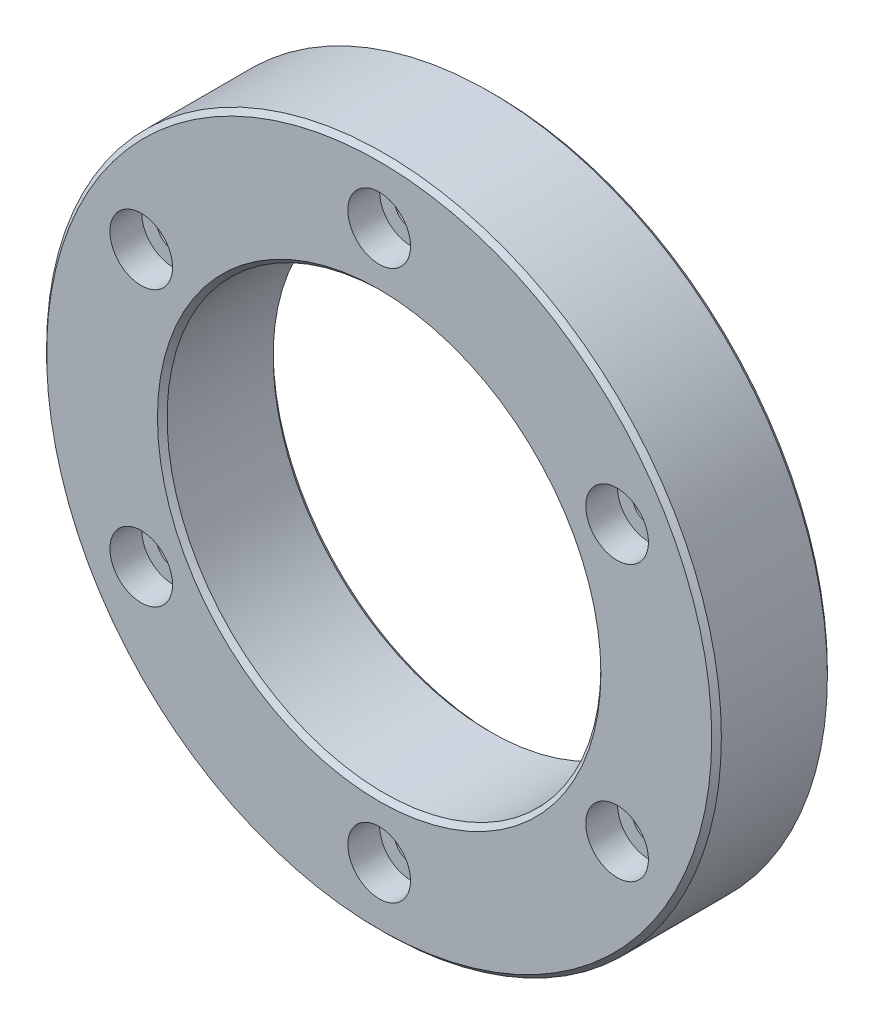
SolidWorks part; units mm, degrees
ref_plane "정면" through (0, 0, 0) normal (0, 0, 1) x (1, 0, 0)
ref_plane "윗면" through (0, 0, 0) normal (0, 1, 0) x (1, 0, 0)
ref_plane "우측면" through (0, 0, 0) normal (1, 0, 0) x (0, 0, -1)
sketch "스케치1" plane through (0, 0, 0) normal (0, 0, 1) x (1, 0, 0)
  circle A0 centre (0, 0) radius 35
  circle A1 centre (0, 0) radius 22.5
  dimension "D1" = 70
  dimension "D2" = 45
extrude "보스-돌출1" add sketch "스케치1" along normal mid plane 12
hole_wizard "M3 육각 소켓 머리 캡 나사용 카운터보어1" positions "스케치3" profile "스케치2" counterbore size "M3" standard "ISO" end condition through all
sketch "스케치3" plane through (0, 0, 6) normal (0, 0, 1) x (1, 0, 0)
  point P0 (0, 28.5)
  dimension "D1" = 28.5
sketch "스케치2" plane through (0, 28.5, 6) normal (1, 0, 0) x (0, -1, 0)
  line L0 (0, 0) -> (0, 12)
  line L1 (0, 12) -> (1.7, 12)
  line L3 (1.7, 12) -> (1.7, 3.3)
  line L4 (1.7, 3.3) -> (3.25, 3.3)
  line L5 (3.25, 3.3) -> (3.25, 0)
  line L7 (3.25, 0) -> (0, 0)
  line L11 (0, -6.35) -> (0, 107.95) construction
  dimension "°üÅë ±¸¸Û Áö¸§" = 3.4
  dimension "°üÅë ±¸¸Û ±íÀÌ" = 12
  dimension "Ä«¿îÅÍº¸¾î Áö¸§" = 6.5
  dimension "Ä«¿îÅÍº¸¾î ±íÀÌ" = 3.3
pattern_circular "원형 패턴1" count 6 over 360 about axis through (0, 0, 0) along (0, 0, 1) of "M3 육각 소켓 머리 캡 나사용 카운터보어1"
chamfer "모따기1" distance 0.5 angle 45 4 edges at (35, 0, -6) (35, 0, 6) (22.5, 0, -6) (22.5, 0, 6)
